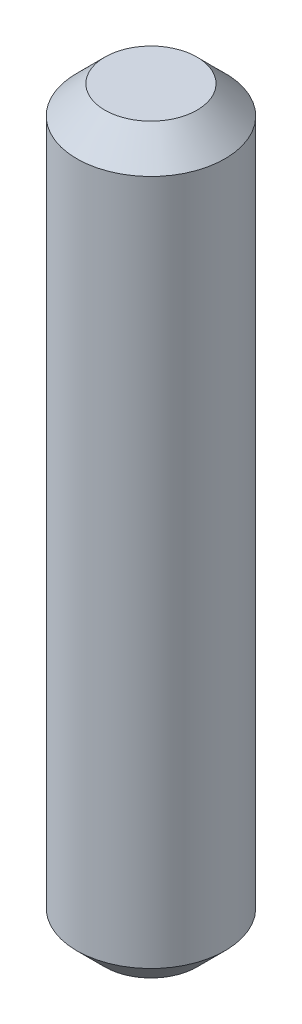
SolidWorks part; units mm, degrees
ref_plane "Front Plane" through (0, 0, 0) normal (0, 0, 1) x (1, 0, 0)
ref_plane "Top Plane" through (0, 0, 0) normal (0, 1, 0) x (1, 0, 0)
ref_plane "Right Plane" through (0, 0, 0) normal (1, 0, 0) x (0, 0, -1)
sketch "Sketch1" plane through (0, 0, 0) normal (0, 1, 0) x (1, 0, 0)
  circle A0 centre (0, 0) radius 1.585
extrude "Boss-Extrude1" add sketch "Sketch1" against normal mid plane 15.87
chamfer "Chamfer1" distance 0.6 angle 45 2 edges at (0, -7.935, 1.585) (0, 7.935, 1.585)
